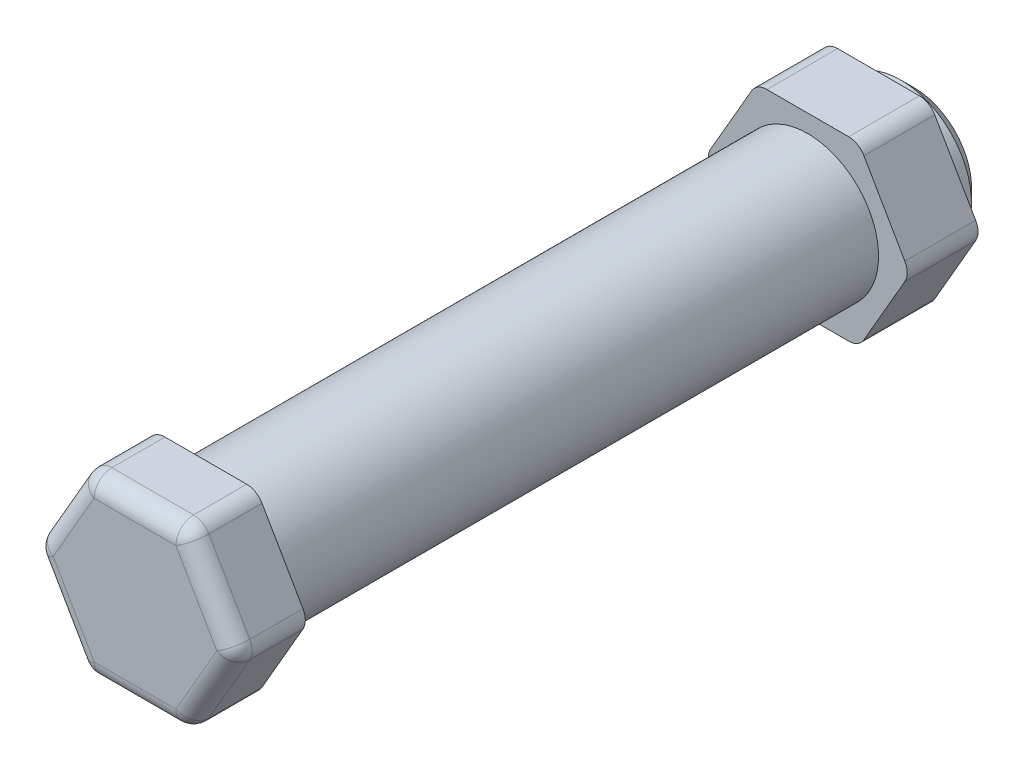
SolidWorks part; units mm, degrees
ref_plane "前视基准面" through (0, 0, 0) normal (0, 0, 1) x (1, 0, 0)
ref_plane "上视基准面" through (0, 0, 0) normal (0, 1, 0) x (1, 0, 0)
ref_plane "右视基准面" through (0, 0, 0) normal (1, 0, 0) x (0, 0, -1)
other "Configuration Table"
ref_plane "基准面1" through (0, 0, 21) normal (0, 0, 1) x (1, 0, 0)
sketch "草图1" plane through (0, 0, 21) normal (0, 0, 1) x (1, 0, 0)
  line L0 (-2.8868, -5) -> (2.8868, -5)
  line L1 (2.8868, -5) -> (5.7735, 0)
  line L2 (5.7735, 0) -> (2.8868, 5)
  line L3 (2.8868, 5) -> (-2.8868, 5)
  line L4 (-2.8868, 5) -> (-5.7735, 0)
  line L5 (-5.7735, 0) -> (-2.8868, -5)
extrude "凸台-拉伸1" add sketch "草图1" against normal blind 4
sketch "草图2" plane through (0, 0, 17) normal (0, 0, -1) x (-1, 0, 0)
  circle A0 centre (0, 0) radius 4
extrude "凸台-拉伸2" add sketch "草图2" along normal blind 34
ref_plane "基准面2" through (0, 0, -17) normal (0, 0, 1) x (1, 0, 0)
sketch "草图3" plane through (0, 0, -17) normal (0, 0, 1) x (1, 0, 0)
  line L0 (-2.8868, -5) -> (2.8868, -5)
  line L1 (2.8868, -5) -> (5.7735, 0)
  line L2 (5.7735, 0) -> (2.8868, 5)
  line L3 (2.8868, 5) -> (-2.8868, 5)
  line L4 (-2.8868, 5) -> (-5.7735, 0)
  line L5 (-5.7735, 0) -> (-2.8868, -5)
extrude "凸台-拉伸3" add sketch "草图3" against normal blind 4
ref_plane "基准面3" through (0, 0, 0) normal (0, -1, 0) x (1, 0, 0)
sketch "草图4" plane through (0, 0, 0) normal (0, -1, 0) x (1, 0, 0)
  line L0 (4, -21) -> (0, -21)
  line L1 (0, -21) -> (0, -23)
  line L2 (0, -23) -> (4, -23)
  line L3 (4, -23) -> (4, -21)
  line L4 (0, -21) -> (0, -23) construction
revolve "旋转1" add sketch "草图4" angle 360 about L4
chamfer "倒角1" distance 0.75 angle 45 1 edges at (-4, 0, -23)
fillet "圆角1" radius 1 18 edges at (-2.8868, 5, 19) (0, 5, 21) (2.8868, 5, 19) (-4.3301, 2.5, 21) (-5.7735, 0, 19) (5.7735, 0, 19) (4.3301, 2.5, 21) (-4.3301, -2.5, 21) (-2.8868, -5, 19) (4.3301, -2.5, 21) (0, -5, 21) (2.8868, -5, 19) (2.8868, 5, -19) (-2.8868, 5, -19) (-2.8868, -5, -19) (2.8868, -5, -19) (5.7735, 0, -19) (-5.7735, 0, -19)
